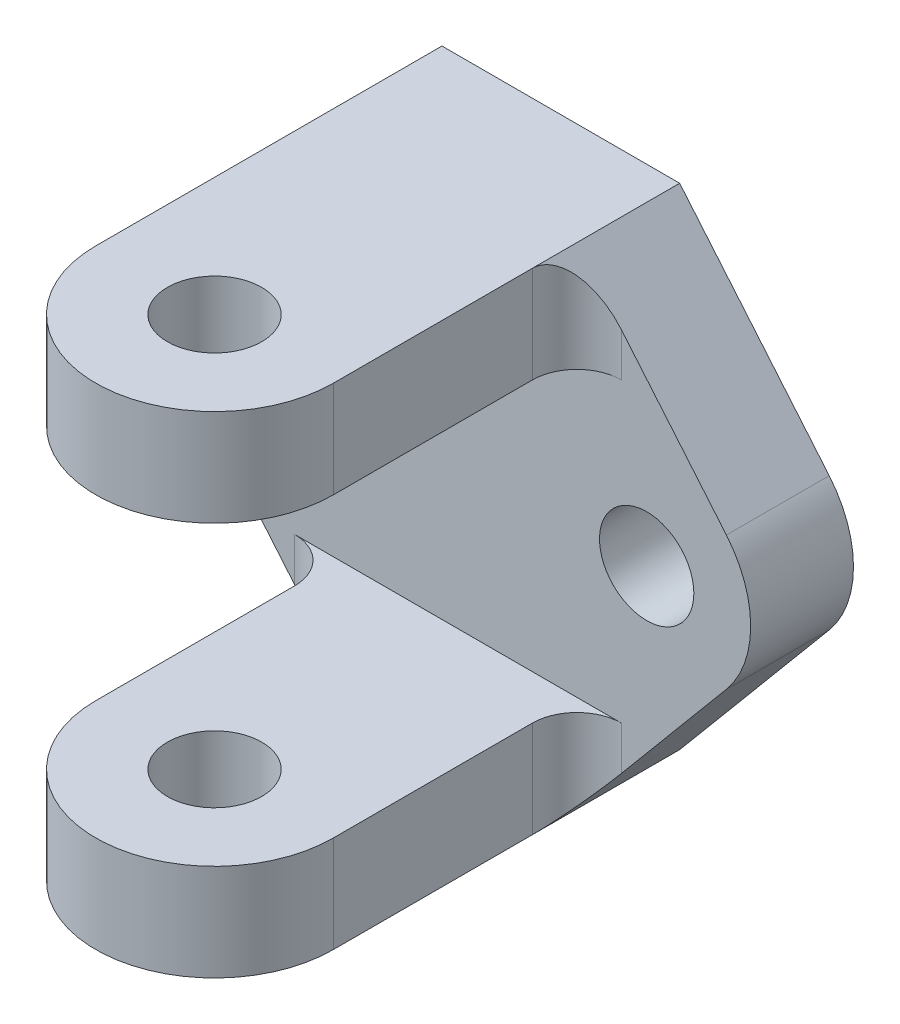
SolidWorks part; units mm, degrees
material "7075-T6 (SN)"
ref_plane "Front Plane" through (0, 0, 0) normal (0, 0, 1) x (1, 0, 0)
ref_plane "Top Plane" through (0, 0, 0) normal (0, 1, 0) x (1, 0, 0)
ref_plane "Right Plane" through (0, 0, 0) normal (1, 0, 0) x (0, 0, -1)
sketch "Sketch1" plane through (0, 0, 0) normal (0, 0, 1) x (1, 0, 0)
  line L0 (12.7, 0) -> (-12.7, 0) construction
  line L1 (-20.7, -16.51) -> (20.7, -16.51)
  line L2 (-20.7, -16.51) -> (-20.7, 16.51)
  line L3 (-20.7, 16.51) -> (20.7, 16.51)
  line L4 (20.7, -16.51) -> (20.7, 16.51)
  line L5 (-20.7, -16.51) -> (20.7, 16.51) construction
  line L6 (-20.7, 16.51) -> (20.7, -16.51) construction
  circle A0 centre (12.7, 0) radius 3.175
  circle A1 centre (-12.7, 0) radius 3.175
  point P0 (0, 0)
  dimension "D1" = 6.35
  dimension "D2" = 25.4
  dimension "D3" = 8
  dimension "D4" = 16.51
extrude "Boss-Extrude1" add sketch "Sketch1" along normal blind 9.46 contours L3 L4 L1 L2
sketch "Sketch2" plane through (0, 0, 9.46) normal (0, 0, 1) x (1, 0, 0)
  line L0 (-12.7, 0) -> (12.7, 0) construction
  line L2 (-20.7, 10) -> (20.7, 10)
  line L3 (-20.7, 10) -> (-20.7, 16.51)
  line L4 (-20.7, 16.51) -> (20.7, 16.51)
  line L5 (20.7, 10) -> (20.7, 16.51)
  line L6 (-20.7, 10) -> (20.7, 16.51) construction
  line L7 (-20.7, 16.51) -> (20.7, 10) construction
  line L8 (-20.7, 16.51) -> (-20.7, -16.51) construction
  line L9 (20.7, -10) -> (20.7, -16.51)
  line L10 (-20.7, -10) -> (-20.7, -16.51)
  line L11 (-20.7, -16.51) -> (20.7, -10) construction
  line L12 (-20.7, -10) -> (20.7, -16.51) construction
  line L13 (-20.7, -10) -> (20.7, -10)
  line L14 (-20.7, -16.51) -> (20.7, -16.51)
  circle A0 centre (-12.7, 0) radius 3.175 construction
  circle A1 centre (12.7, 0) radius 3.175 construction
  point P6 (0, 13.255)
  point P21 (0, -13.255)
  dimension "D1" = 20
extrude "Boss-Extrude2" add sketch "Sketch2" along normal blind 53
sketch "Sketch3" plane through (0, 0, 0) normal (0, 1, 0) x (1, 0, 0)
  point P0 (0, -25.8481)
  dimension "D1" = 25.8481
ref_point "UBJ Point"
sketch "Sketch4" plane through (0, 0, 0) normal (0, 1, 0) x (1, 0, 0)
  circle A0 centre (0, -25.8481) radius 3.175
  dimension "D1" = 6.35
extrude "Cut-Extrude1" cut sketch "Sketch4" against normal up to surface and the other way up to surface up to face at (0, -16.51, 31.23) other way up to face at (0, 16.51, 31.23)
sketch "Sketch5" plane through (0, 0, 0) normal (0, 1, 0) x (1, 0, 0)
  line L0 (20.7, -9.46) -> (7.84, -30.6142)
  line L1 (-7.84, -30.6142) -> (-20.7, -9.46)
  line L4 (20.7, 0) -> (-20.7, 0)
  line L5 (-20.7, 0) -> (-20.7, -62.46)
  line L6 (-20.7, -62.46) -> (20.7, -62.46)
  line L7 (20.7, -62.46) -> (20.7, 0)
  line L9 (-20.7, -9.46) -> (-20.7, -62.46)
  line L10 (-20.7, -62.46) -> (20.7, -62.46)
  line L11 (20.7, -62.46) -> (20.7, -9.46)
  line L12 (20.7, -9.46) -> (-20.7, -9.46)
  line L13 (20.7, -62.46) -> (20.7, -9.46)
  line L14 (-20.7, -62.46) -> (20.7, -62.46)
  line L15 (-20.7, -9.46) -> (-20.7, -62.46)
  line L17 (20.7, -62.46) -> (20.7, -9.46)
  line L18 (-20.7, -62.46) -> (20.7, -62.46)
  line L19 (-20.7, -9.46) -> (-20.7, -62.46)
  arc A0 (-7.84, -30.6142) -> (7.84, -30.6142) centre (0, -25.8481) ccw
  circle A1 centre (0, -25.8481) radius 3.175 construction
  circle A2 centre (0, -25.8481) radius 3.175 construction
  dimension "D3" = 6
  dimension "D1" = 0
  dimension "D2" = 0
extrude "Cut-Extrude2" [suppressed] cut sketch "Sketch5" against normal up to surface and the other way up to surface contours A0 L1 L9 L10 L11 L0
sketch "Sketch6" plane through (0, 0, 0) normal (0, 1, 0) x (1, 0, 0)
  line L0 (-8, -25.8481) -> (-8, -17.46)
  line L1 (8, -25.8481) -> (8, -17.46)
  line L2 (-16, -9.46) -> (-20.7, -9.46)
  line L3 (-8, -17.46) -> (-8, -9.46)
  line L4 (20.7, -9.46) -> (-20.7, -9.46)
  line L5 (-20.7, -9.46) -> (-20.7, -62.46)
  line L6 (-20.7, -62.46) -> (20.7, -62.46)
  line L7 (20.7, -62.46) -> (20.7, -9.46)
  line L8 (20.7, -9.46) -> (16, -9.46)
  line L9 (-20.7, -9.46) -> (-20.7, -62.46)
  line L10 (-20.7, -62.46) -> (20.7, -62.46)
  line L11 (20.7, -62.46) -> (20.7, -9.46)
  line L12 (-8, -9.46) -> (-16, -9.46)
  line L13 (8, -17.46) -> (8, -9.46)
  line L14 (8, -9.46) -> (16, -9.46)
  arc A0 (-8, -25.8481) -> (8, -25.8481) centre (0, -25.8481) ccw
  circle A1 centre (0, -25.8481) radius 3.175 construction
  arc A2 (-8, -17.46) -> (-16, -9.46) centre (-16, -17.46) ccw construction
  arc A3 (8, -17.46) -> (16, -9.46) centre (16, -17.46) cw construction
  dimension "D2" = 8
  dimension "D3" = 8
  dimension "D1" = 0
extrude "Cut-Extrude3" cut sketch "Sketch6" against normal up to surface and the other way up to surface
fillet "Fillet1" [suppressed] radius 12.7
sketch "Sketch7" plane through (0, 0, 0) normal (0, 0, 1) x (1, 0, 0)
  line L0 (-12.7, 7) -> (-8, 7)
  line L1 (-12.7, -7) -> (-8, -7)
  line L2 (-8, 10) -> (-8, 7)
  line L3 (-8, -10) -> (-8, -7)
  line L4 (0, 10.3988) -> (0, -8.4154) construction
  line L5 (8, -10) -> (8, -7)
  line L6 (8, 10) -> (8, 16.51)
  line L7 (20.7, 16.51) -> (20.7, -16.51)
  line L8 (8, -10) -> (8, -16.51)
  line L9 (8, 10) -> (8, 7)
  line L10 (12.7, 7) -> (8, 7)
  line L11 (12.7, -7) -> (8, -7)
  line L12 (8, 10) -> (-8, 10)
  line L15 (-20.7, 16.51) -> (-20.7, -16.51)
  line L18 (-8, -10) -> (8, -10)
  line L21 (20.7, -16.51) -> (20.7, 16.51)
  line L27 (-20.7, 16.51) -> (-20.7, -16.51)
  line L33 (20.7, -16.51) -> (20.7, 16.51)
  line L36 (-8, 16.51) -> (-8, 10)
  line L37 (-8, -10) -> (-8, -16.51)
  line L48 (-8, 10) -> (-8, 16.51)
  line L49 (-8, -16.51) -> (-8, -10)
  line L52 (-8, 16.51) -> (-20.7, 16.51)
  line L53 (-8, 16.51) -> (-20.7, 16.51)
  line L54 (-20.7, -16.51) -> (-8, -16.51)
  line L55 (-20.7, -16.51) -> (-8, -16.51)
  line L56 (8, -10) -> (8, -16.51)
  line L57 (8, -16.51) -> (20.7, -16.51)
  line L58 (8, -16.51) -> (20.7, -16.51)
  line L59 (20.7, 16.51) -> (8, 16.51)
  line L60 (20.7, 16.51) -> (8, 16.51)
  line L61 (8, 16.51) -> (8, 10)
  arc A0 (-12.7, 7) -> (-12.7, -7) centre (-12.7, 0) ccw
  circle A1 centre (-12.7, 0) radius 3.175 construction
  arc A2 (12.7, 7) -> (12.7, -7) centre (12.7, 0) cw
  dimension "D2" = 7
  dimension "D1" = 0
extrude "Cut-Extrude4" cut sketch "Sketch7" along normal up to surface (9.46 mm away)
fillet "Fillet2" [suppressed] radius 5
sketch "Sketch8" plane through (0, 0, 0) normal (0, 0, 1) x (1, 0, 0)
  line L0 (12.7, 7) -> (8, 7) construction
  line L1 (8, 16.51) -> (8, 7) construction
  line L2 (12.7, 7) -> (8, 7)
  line L3 (8, 16.51) -> (8, 7)
  line L4 (6.7586, 0) -> (-5.803, 0) construction
  line L5 (0, 7.1591) -> (0, -7.1591) construction
  line L6 (8, 16.51) -> (18.0658, 4.4954)
  line L7 (-8, 16.51) -> (-8, 7)
  line L8 (-12.7, 7) -> (-8, 7)
  line L9 (-8, 16.51) -> (-18.0658, 4.4954)
  line L10 (-8, -16.51) -> (-18.0658, -4.4954)
  line L11 (-12.7, -7) -> (-8, -7)
  line L12 (-8, -16.51) -> (-8, -7)
  line L13 (8, -16.51) -> (8, -7)
  line L14 (12.7, -7) -> (8, -7)
  line L15 (8, -16.51) -> (18.0658, -4.4954)
  arc A0 (12.7, -7) -> (12.7, 7) centre (12.7, 0) ccw construction
  arc A1 (18.0658, 4.4954) -> (12.7, 7) centre (12.7, 0) ccw
  arc A2 (-18.0658, 4.4954) -> (-12.7, 7) centre (-12.7, 0) cw
  arc A3 (-18.0658, -4.4954) -> (-12.7, -7) centre (-12.7, 0) ccw
  arc A4 (18.0658, -4.4954) -> (12.7, -7) centre (12.7, 0) cw
extrude "Boss-Extrude3" add sketch "Sketch8" along normal up to surface (9.46 mm away) contours L15 A4 L14 L13 | A3 L10 L12 L11 | L6 A1 L2 L3 | L9 A2 L8 L7 up to face at (0, 0, 9.46)
fillet "Fillet3" radius 3 4 edges at (8, 13.255, 9.46) (-8, 13.255, 9.46) (-8, -13.255, 9.46) (8, -13.255, 9.46)
sketch "Sketch10" plane through (0, 0, 0) normal (0, 0, 1) x (1, 0, 0)
  line L5 (-8, 16.51) -> (-18.0658, 4.4954)
  line L6 (-8, 16.51) -> (-18.0658, 4.4954)
  line L7 (8, 16.51) -> (-8, 16.51)
  line L8 (18.0658, 4.4954) -> (8, 16.51)
  line L9 (8, -16.51) -> (18.0658, -4.4954)
  line L10 (-8, -16.51) -> (8, -16.51)
  line L13 (8, 16.51) -> (-8, 16.51)
  line L14 (18.0658, 4.4954) -> (8, 16.51)
  line L15 (8, -16.51) -> (18.0658, -4.4954)
  line L16 (-8, -16.51) -> (8, -16.51)
  line L18 (-18.0658, -4.4954) -> (-8, -16.51)
  line L19 (-18.0658, -4.4954) -> (-8, -16.51)
  arc A2 (-18.0658, 4.4954) -> (-18.0658, -4.4954) centre (-12.7, 0) ccw
  arc A3 (18.0658, -4.4954) -> (18.0658, 4.4954) centre (12.7, 0) ccw
  arc A5 (18.0658, -4.4954) -> (18.0658, 4.4954) centre (12.7, 0) ccw
  arc A6 (-18.0658, 4.4954) -> (-18.0658, -4.4954) centre (-12.7, 0) ccw
  dimension "D1" = 0
extrude "Cut-Extrude5" cut sketch "Sketch10" along normal blind 2.54
